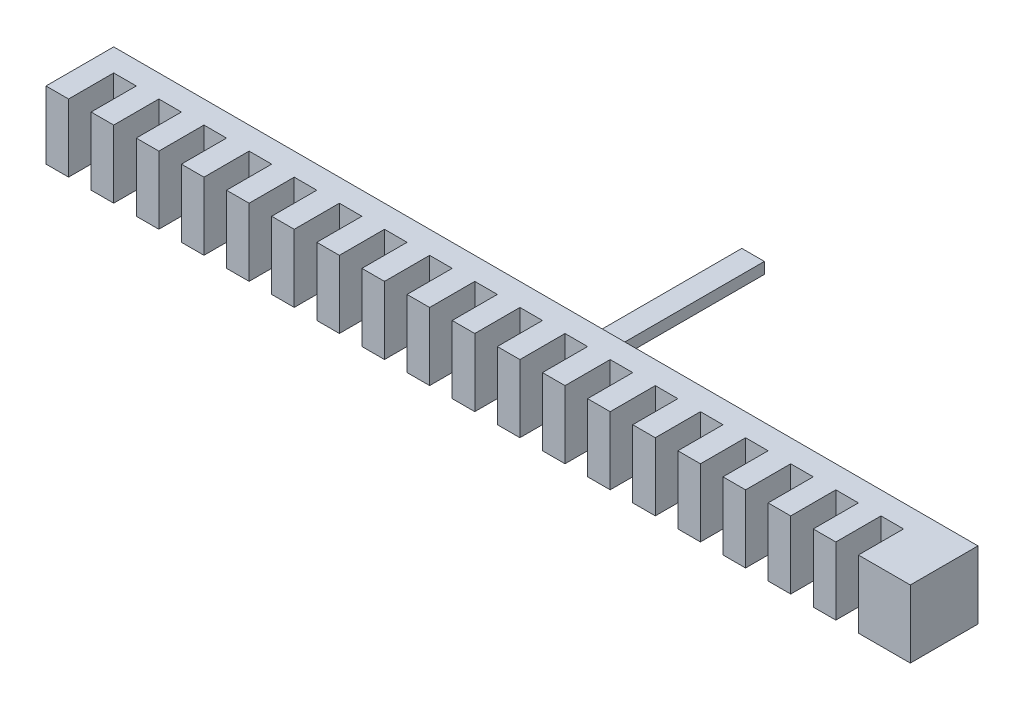
SolidWorks part; units mm, degrees
ref_plane "Plan de face" through (0, 0, 0) normal (0, 0, 1) x (1, 0, 0)
ref_plane "Plan de dessus" through (0, 0, 0) normal (0, 1, 0) x (1, 0, 0)
ref_plane "Plan de droite" through (0, 0, 0) normal (1, 0, 0) x (0, 0, -1)
sketch "Esquisse1" plane through (0, 0, 0) normal (0, 0, 1) x (1, 0, 0)
  line L1 (-191.5, 15) -> (191.5, 15)
  line L2 (-191.5, 15) -> (-191.5, -15)
  line L3 (-191.5, -15) -> (191.5, -15)
  line L4 (191.5, 15) -> (191.5, -15)
  point P4 (0, 15)
  point P6 (-191.5, 0)
  dimension "D1" = 383
  dimension "D2" = 30
extrude "Boss.-Extru.1" add sketch "Esquisse1" along normal blind 10
sketch "Esquisse2" plane through (0, 0, 10) normal (0, 0, 1) x (1, 0, 0)
  line L0 (-191.5, -15) -> (191.5, -15) construction
  line L1 (-191.5, 15) -> (-181.5, 15)
  line L2 (-191.5, 15) -> (-191.5, -15)
  line L3 (-191.5, -15) -> (-181.5, -15)
  line L4 (-181.5, 15) -> (-181.5, -15)
  line L5 (-171.5, -15) -> (-161.5, -15)
  line L6 (-161.5, 15) -> (-161.5, -15)
  line L7 (-171.5, 15) -> (-171.5, -15)
  line L8 (-171.5, 15) -> (-161.5, 15)
  line L9 (-151.5, -15) -> (-141.5, -15)
  line L10 (-141.5, 15) -> (-141.5, -15)
  line L11 (-151.5, 15) -> (-151.5, -15)
  line L12 (-151.5, 15) -> (-141.5, 15)
  line L13 (-131.5, -15) -> (-121.5, -15)
  line L14 (-121.5, 15) -> (-121.5, -15)
  line L15 (-131.5, 15) -> (-131.5, -15)
  line L16 (-131.5, 15) -> (-121.5, 15)
  line L17 (-111.5, -15) -> (-101.5, -15)
  line L18 (-101.5, 15) -> (-101.5, -15)
  line L19 (-111.5, 15) -> (-111.5, -15)
  line L20 (-111.5, 15) -> (-101.5, 15)
  line L21 (-91.5, -15) -> (-81.5, -15)
  line L22 (-81.5, 15) -> (-81.5, -15)
  line L23 (-91.5, 15) -> (-91.5, -15)
  line L24 (-91.5, 15) -> (-81.5, 15)
  line L25 (-71.5, -15) -> (-61.5, -15)
  line L26 (-61.5, 15) -> (-61.5, -15)
  line L27 (-71.5, 15) -> (-71.5, -15)
  line L28 (-71.5, 15) -> (-61.5, 15)
  line L29 (-51.5, -15) -> (-41.5, -15)
  line L30 (-41.5, 15) -> (-41.5, -15)
  line L31 (-51.5, 15) -> (-51.5, -15)
  line L32 (-51.5, 15) -> (-41.5, 15)
  line L33 (-31.5, -15) -> (-21.5, -15)
  line L34 (-21.5, 15) -> (-21.5, -15)
  line L35 (-31.5, 15) -> (-31.5, -15)
  line L36 (-31.5, 15) -> (-21.5, 15)
  line L37 (-11.5, -15) -> (-1.5, -15)
  line L38 (-1.5, 15) -> (-1.5, -15)
  line L39 (-11.5, 15) -> (-11.5, -15)
  line L40 (-11.5, 15) -> (-1.5, 15)
  line L41 (8.5, -15) -> (18.5, -15)
  line L42 (18.5, 15) -> (18.5, -15)
  line L43 (8.5, 15) -> (8.5, -15)
  line L44 (8.5, 15) -> (18.5, 15)
  line L45 (28.5, -15) -> (38.5, -15)
  line L46 (38.5, 15) -> (38.5, -15)
  line L47 (28.5, 15) -> (28.5, -15)
  line L48 (28.5, 15) -> (38.5, 15)
  line L49 (48.5, -15) -> (58.5, -15)
  line L50 (58.5, 15) -> (58.5, -15)
  line L51 (48.5, 15) -> (48.5, -15)
  line L52 (48.5, 15) -> (58.5, 15)
  line L53 (68.5, -15) -> (78.5, -15)
  line L54 (78.5, 15) -> (78.5, -15)
  line L55 (68.5, 15) -> (68.5, -15)
  line L56 (68.5, 15) -> (78.5, 15)
  line L57 (88.5, -15) -> (98.5, -15)
  line L58 (98.5, 15) -> (98.5, -15)
  line L59 (88.5, 15) -> (88.5, -15)
  line L60 (88.5, 15) -> (98.5, 15)
  line L61 (108.5, -15) -> (118.5, -15)
  line L62 (118.5, 15) -> (118.5, -15)
  line L63 (108.5, 15) -> (108.5, -15)
  line L64 (108.5, 15) -> (118.5, 15)
  line L65 (128.5, -15) -> (138.5, -15)
  line L66 (138.5, 15) -> (138.5, -15)
  line L67 (128.5, 15) -> (128.5, -15)
  line L68 (128.5, 15) -> (138.5, 15)
  line L69 (148.5, -15) -> (158.5, -15)
  line L70 (158.5, 15) -> (158.5, -15)
  line L71 (148.5, 15) -> (148.5, -15)
  line L72 (148.5, 15) -> (158.5, 15)
  line L73 (168.5, -15) -> (178.5, -15)
  line L74 (178.5, 15) -> (191.5, 15)
  line L75 (168.5, 15) -> (168.5, -15)
  line L76 (168.5, 15) -> (178.5, 15)
  line L77 (191.5, 15) -> (191.5, -15)
  line L78 (191.5, -15) -> (178.5, -15)
  line L81 (188.5, -15) -> (198.5, -15) [skipped]
  line L82 (198.5, 15) -> (198.5, -15) [skipped]
  line L83 (188.5, 15) -> (188.5, -15) [skipped]
  line L84 (188.5, 15) -> (198.5, 15) [skipped]
  line L86 (178.5, 15) -> (178.5, -15) [skipped]
  dimension "D1" = 10
  dimension "D2" = 20
extrude "Boss.-Extru.2" add sketch "Esquisse2" along normal blind 20
sketch "Esquisse3" plane through (0, -15, 0) normal (0, -1, 0) x (1, 0, 0)
  line L1 (5, 8.163) -> (-5, 8.163)
  line L2 (5, 8.163) -> (5, -91.837)
  line L3 (5, -91.837) -> (-5, -91.837)
  line L4 (-5, 8.163) -> (-5, -91.837)
  point P6 (0, -91.837)
  dimension "D1" = 100
  dimension "D2" = 10
extrude "Boss.-Extru.3" add sketch "Esquisse3" along normal blind 5
